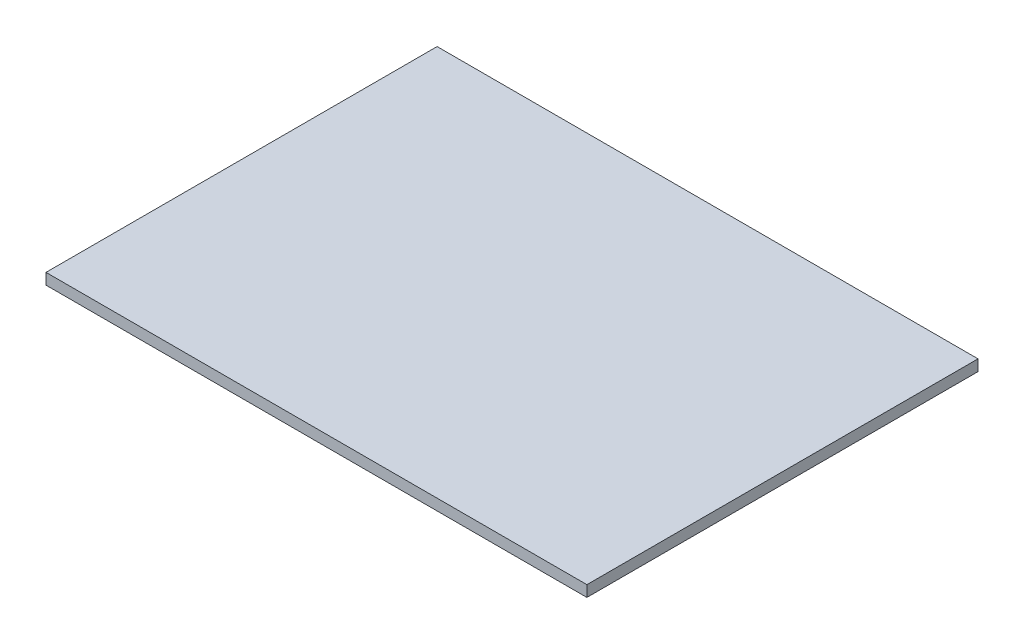
SolidWorks part; units mm, degrees
material "橡木"
ref_plane "前视基准面" through (0, 0, 0) normal (0, 0, 1) x (1, 0, 0)
ref_plane "上视基准面" through (0, 0, 0) normal (0, 1, 0) x (1, 0, 0)
ref_plane "右视基准面" through (0, 0, 0) normal (1, 0, 0) x (0, 0, -1)
other "Configuration Table"
sketch "草图1" plane through (0, 0, 0) normal (0, 1, 0) x (1, 0, 0)
  line L1 (0, 0) -> (975, 0)
  line L2 (0, 0) -> (0, 705)
  line L3 (0, 705) -> (975, 705)
  line L4 (975, 0) -> (975, 705)
  dimension "D1" = 975
  dimension "D2" = 705
extrude "凸台-拉伸1" add sketch "草图1" along normal blind 20
